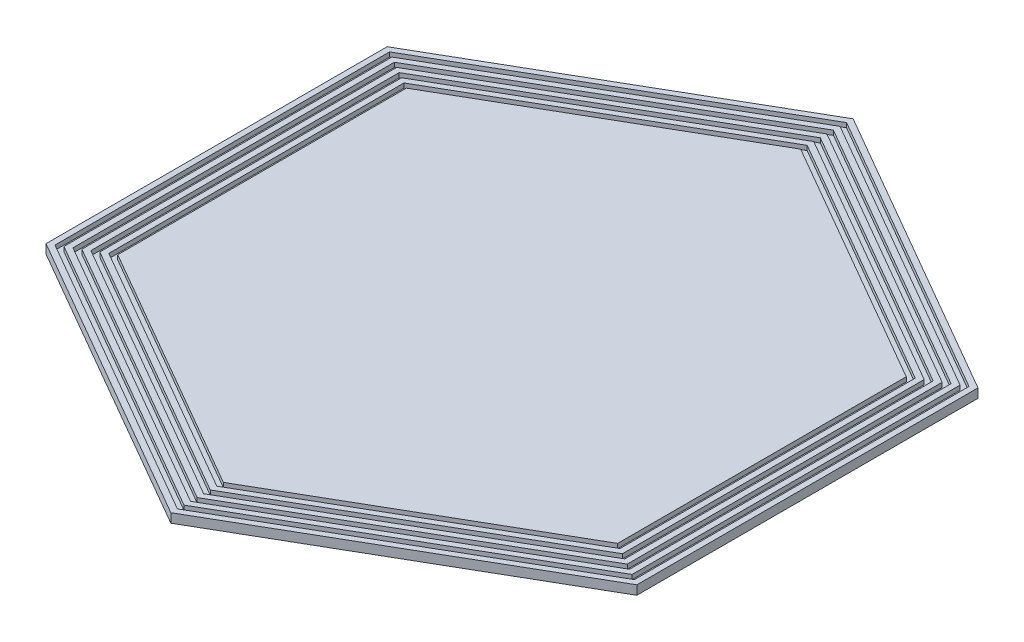
SolidWorks part; units mm, degrees
ref_plane "Front Plane" through (0, 0, 0) normal (0, 0, 1) x (1, 0, 0)
ref_plane "Top Plane" through (0, 0, 0) normal (0, 1, 0) x (1, 0, 0)
ref_plane "Right Plane" through (0, 0, 0) normal (1, 0, 0) x (0, 0, -1)
sketch "Sketch1" plane through (0, 0, 0) normal (0, 1, 0) x (1, 0, 0)
  line L1 (0, -60) -> (51.9615, -30)
  line L2 (51.9615, -30) -> (51.9615, 30)
  line L3 (51.9615, 30) -> (0, 60)
  line L4 (0, 60) -> (-51.9615, 30)
  line L5 (-51.9615, 30) -> (-51.9615, -30)
  line L6 (-51.9615, -30) -> (0, -60)
  circle A0 centre (0, 0) radius 60 construction
  dimension "D1" = 120
extrude "Boss-Extrude1" add sketch "Sketch1" along normal blind 1.6
sketch "Sketch2" plane through (0, 1.6, 0) normal (0, 1, 0) x (1, 0, 0)
  line L6 (-49.9615, -28.8453) -> (0, -57.6906)
  line L7 (0, -57.6906) -> (49.9615, -28.8453)
  line L8 (49.9615, -28.8453) -> (49.9615, 28.8453)
  line L9 (49.9615, 28.8453) -> (0, 57.6906)
  line L10 (0, 57.6906) -> (-49.9615, 28.8453)
  line L11 (-49.9615, 28.8453) -> (-49.9615, -28.8453)
  line L12 (-50.9615, -29.4226) -> (0, -58.8453)
  line L13 (0, -58.8453) -> (50.9615, -29.4226)
  line L14 (50.9615, -29.4226) -> (50.9615, 29.4226)
  line L15 (50.9615, 29.4226) -> (0, 58.8453)
  line L16 (0, 58.8453) -> (-50.9615, 29.4226)
  line L17 (-50.9615, 29.4226) -> (-50.9615, -29.4226)
  line L18 (-50.9615, -29.4226) -> (0, -58.8453)
  line L19 (0, -58.8453) -> (50.9615, -29.4226)
  line L20 (50.9615, -29.4226) -> (50.9615, 29.4226)
  line L21 (50.9615, 29.4226) -> (0, 58.8453)
  line L22 (0, 58.8453) -> (-50.9615, 29.4226)
  line L23 (-50.9615, 29.4226) -> (-50.9615, -29.4226)
  line L24 (-47.9615, -27.6906) -> (0, -55.3812)
  line L25 (0, -55.3812) -> (47.9615, -27.6906)
  line L26 (47.9615, -27.6906) -> (47.9615, 27.6906)
  line L27 (47.9615, 27.6906) -> (0, 55.3812)
  line L28 (0, 55.3812) -> (-47.9615, 27.6906)
  line L29 (-47.9615, 27.6906) -> (-47.9615, -27.6906)
  line L30 (-48.9615, -28.2679) -> (0, -56.5359)
  line L31 (0, -56.5359) -> (48.9615, -28.2679)
  line L32 (48.9615, -28.2679) -> (48.9615, 28.2679)
  line L33 (48.9615, 28.2679) -> (0, 56.5359)
  line L34 (0, 56.5359) -> (-48.9615, 28.2679)
  line L35 (-48.9615, 28.2679) -> (-48.9615, -28.2679)
  line L36 (-45.9615, -26.5359) -> (0, -53.0718)
  line L37 (0, -53.0718) -> (45.9615, -26.5359)
  line L38 (45.9615, -26.5359) -> (45.9615, 26.5359)
  line L39 (45.9615, 26.5359) -> (0, 53.0718)
  line L40 (0, 53.0718) -> (-45.9615, 26.5359)
  line L41 (-45.9615, 26.5359) -> (-45.9615, -26.5359)
  line L42 (-46.9615, -27.1132) -> (0, -54.2265)
  line L43 (0, -54.2265) -> (46.9615, -27.1132)
  line L44 (46.9615, -27.1132) -> (46.9615, 27.1132)
  line L45 (46.9615, 27.1132) -> (0, 54.2265)
  line L46 (0, 54.2265) -> (-46.9615, 27.1132)
  line L47 (-46.9615, 27.1132) -> (-46.9615, -27.1132)
  line L48 (-43.9615, -25.3812) -> (0, -50.7624)
  line L49 (0, -50.7624) -> (43.9615, -25.3812)
  line L50 (43.9615, -25.3812) -> (43.9615, 25.3812)
  line L51 (43.9615, 25.3812) -> (0, 50.7624)
  line L52 (0, 50.7624) -> (-43.9615, 25.3812)
  line L53 (-43.9615, 25.3812) -> (-43.9615, -25.3812)
  line L54 (-44.9615, -25.9585) -> (0, -51.9171)
  line L55 (0, -51.9171) -> (44.9615, -25.9585)
  line L56 (44.9615, -25.9585) -> (44.9615, 25.9585)
  line L57 (44.9615, 25.9585) -> (0, 51.9171)
  line L58 (0, 51.9171) -> (-44.9615, 25.9585)
  line L59 (-44.9615, 25.9585) -> (-44.9615, -25.9585)
  dimension "D1" = 1
  dimension "D2" = 1
  dimension "D3" = 2
  dimension "D4" = 4
extrude "Cut-Extrude1" cut sketch "Sketch2" against normal blind 0.8 contours L22 L23 L18 L19 L20 L21 L11 L10 L9 L8 L7 L6 | L34 L35 L30 L31 L32 L33 L29 L28 L27 L26 L25 L24 | L46 L47 L42 L43 L44 L45 L41 L40 L39 L38 L37 L36 | L58 L59 L54 L55 L56 L57 L53 L52 L51 L50 L49 L48
